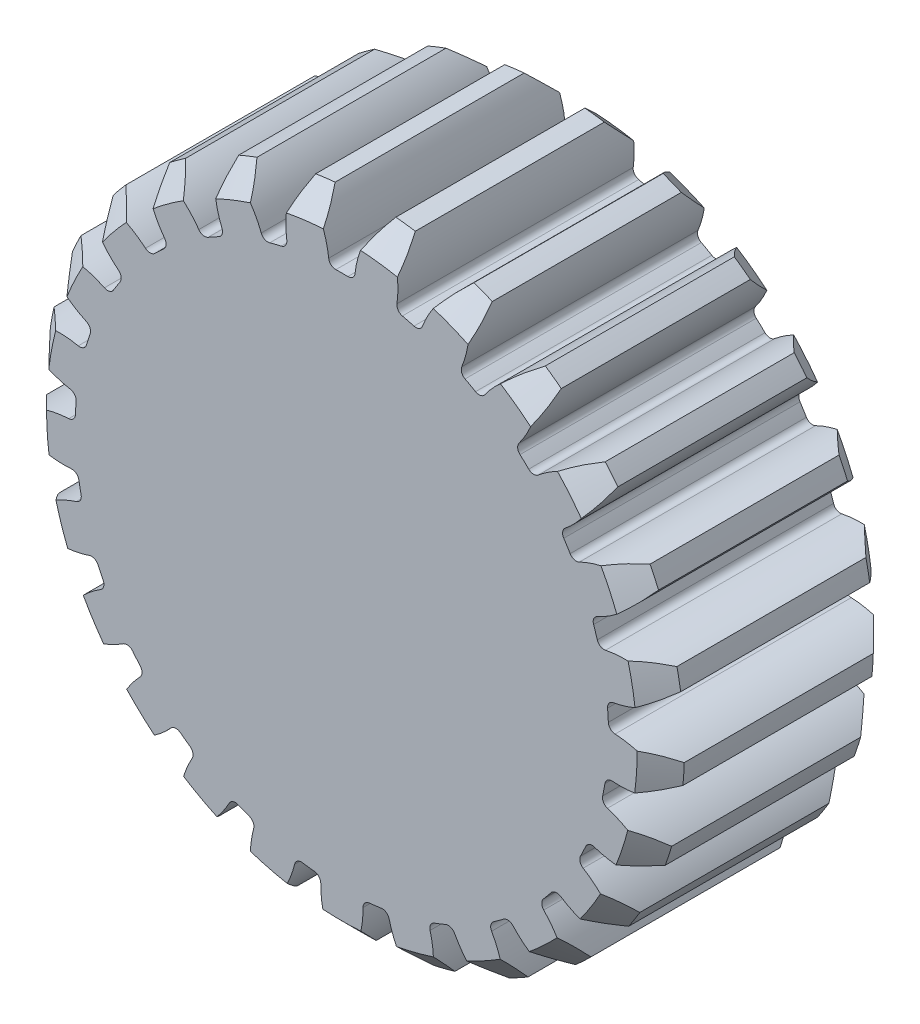
SolidWorks part; units mm, degrees
material "Plain Carbon Steel"
ref_plane "Front Plane" through (0, 0, 0) normal (0, 0, 1) x (1, 0, 0)
ref_plane "Top Plane" through (0, 0, 0) normal (0, 1, 0) x (1, 0, 0)
ref_plane "Right Plane" through (0, 0, 0) normal (1, 0, 0) x (0, 0, -1)
sketch "Sketch2" plane through (0, 0, 0) normal (0, 0, 1) x (1, 0, 0)
  circle A0 centre (0, 0) radius 25 construction
  circle A1 centre (0, 0) radius 27
  dimension "D1" = 50
  dimension "D2" = 54
extrude "Boss-Extrude1" add sketch "Sketch2" along normal mid plane 20
sketch "Sketch3" plane through (0, 0, 0) normal (0, 0, 1) x (1, 0, 0)
  line L0 (0, 0) -> (0, 27) construction
  line L1 (0, 0) -> (6.7146, 26.1517) construction
  line L2 (0, 0) -> (3.384, 26.7871) construction
  line L3 (-1.072, 22.4744) -> (0, 0) construction
  line L4 (-1.5698, 24.9507) -> (1.5698, 24.9507) construction
  line L5 (1.5698, 24.9507) -> (4.6845, 24.5572) construction
  line L6 (-2.2805, 26.9035) -> (0, 20.6378) construction
  circle A0 centre (0, 0) radius 23
  circle A2 centre (0, 0) radius 27 construction
  arc A3 (-2.5691, 26.8775) -> (-1.072, 22.4744) centre (-9.4743, 22.0737) cw
  circle A4 centre (0, 0) radius 27 construction
  arc A5 (2.5691, 26.8775) -> (1.072, 22.4744) centre (9.4743, 22.0737) ccw
  circle A6 centre (0, 0) radius 25 construction
  arc A7 (-2.5691, 26.8775) -> (2.5691, 26.8775) centre (0, 0) cw
  arc A8 (1.072, 22.4744) -> (-1.072, 22.4744) centre (0, 0) ccw
  dimension "D1" = 14.4
  dimension "D2" = 4
  dimension "D5" = 20
sketch "Sketch4" plane through (0, 0, 0) normal (0, 0, 1) x (1, 0, 0)
extrude "Cut-Extrude1" cut sketch "Sketch3" against normal through all both and the other way through all contours A5 A8 A3 A7
fillet "Fillet1" radius 0.6 2 edges at (-1.072, 22.4744, 0) (1.072, 22.4744, 0)
chamfer "Chamfer1" distance 2 2 edges at (0, -27, 10) (0, -27, -10)
pattern_circular "CirPattern2" count 25 over 360 about axis through (0, -0.075, 0) along (0, 0, 1) of "Fillet1", "Cut-Extrude1"
equation "\"module\"= 2mm"
equation "\"number of teeth\"= 25'p"
equation "\"pressure angle\"= 20"
equation "\"D1@Sketch2\"=\"module\" *\"number of teeth\""
equation "\"D2@Sketch2\"=(\"number of teeth\" + 2 ) * \"module\""
equation "\"D1@Sketch3\"=360 / \"number of teeth\""
equation "\"D2@Sketch3\"=\"module\" * 2"
equation "\"D5@Sketch3\"=\"pressure angle\""
equation "\"D1@Fillet1\"=0.3 * \"module\""
equation "\"D1@CirPattern2\"=\"number of teeth\""
equation "\"D1@Chamfer1\"=\"module\""
